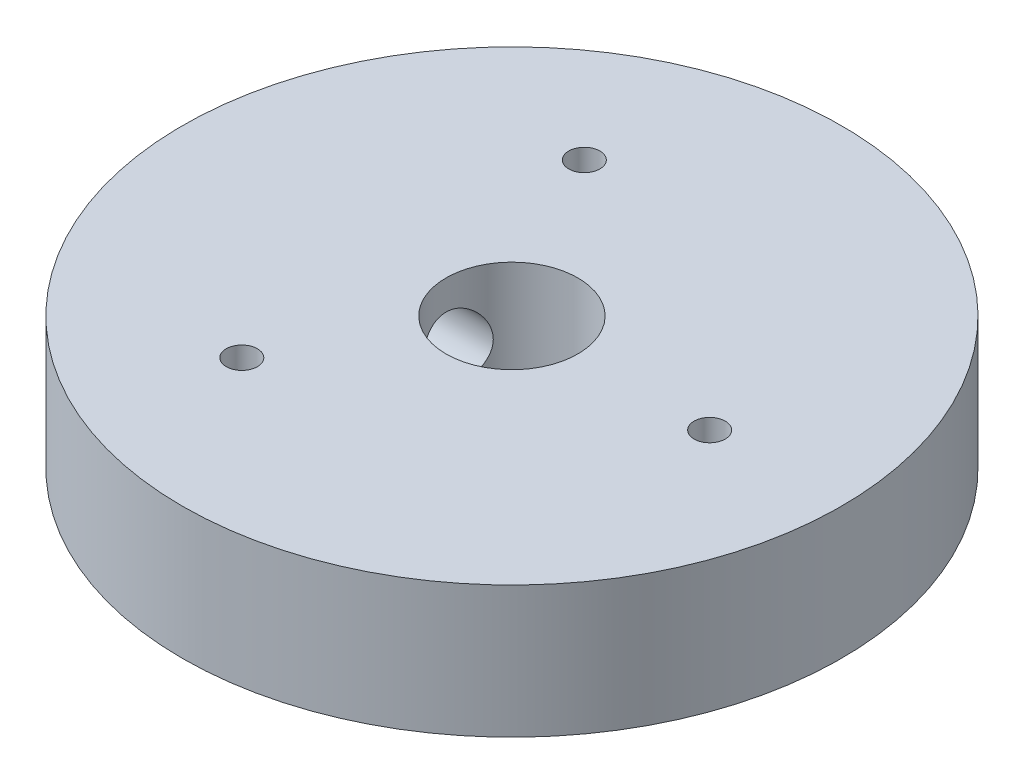
SolidWorks part; units mm, degrees
ref_plane "Front Plane" through (0, 0, 0) normal (0, 0, 1) x (1, 0, 0)
ref_plane "Top Plane" through (0, 0, 0) normal (0, 1, 0) x (1, 0, 0)
ref_plane "Right Plane" through (0, 0, 0) normal (1, 0, 0) x (0, 0, -1)
sketch "Sketch1" plane through (0, 0, 0) normal (0, 1, 0) x (1, 0, 0)
  circle A0 centre (0, 0) radius 3.175
  circle A1 centre (0, 0) radius 15.875
  circle A2 centre (9.525, 0) radius 0.7504
  circle A3 centre (-4.7625, -8.2489) radius 0.7504
  circle A4 centre (-4.7625, 8.2489) radius 0.7504
  point P12 (0, 0)
  dimension "D1" = 6.35
  dimension "D2" = 31.75
  dimension "D3" = 9.525
  dimension "D4" = 3
extrude "Boss-Extrude2" add sketch "Sketch1" along normal mid plane 6.35
sketch "Sketch3" plane through (0, 0, 0) normal (1, 0, 0) x (0, 0, -1)
  circle A0 centre (0, 0) radius 1.75
  dimension "D1" = 3.5
extrude "Cut-Extrude1" cut sketch "Sketch3" against normal through all
equation "\"tightTol\" = 0.005in"
equation "\"normTol\"= 0.01in"
equation "\"looseTol\"= 0.02in"
equation "\"D1@Sketch1\"=0.2500in"
equation "\"D1@Sketch3\"=3.5mm"
